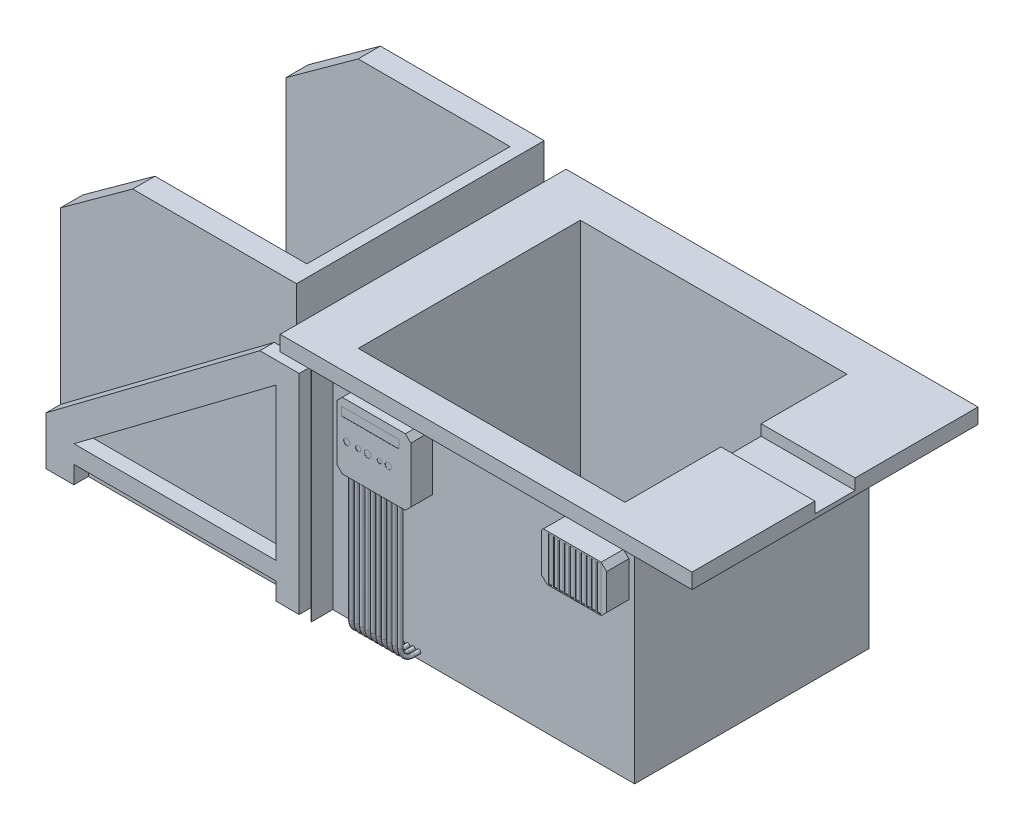
SolidWorks part; units mm, degrees
ref_plane "Alzado" through (0, 0, 0) normal (0, 0, 1) x (1, 0, 0)
ref_plane "Planta" through (0, 0, 0) normal (0, 1, 0) x (1, 0, 0)
ref_plane "Vista lateral" through (0, 0, 0) normal (1, 0, 0) x (0, 0, -1)
sketch "Croquis1" plane through (0, 0, 0) normal (0, 0, 1) x (1, 0, 0)
  line L0 (-486.3336, -748) -> (-486.3336, 440.4157)
  line L1 (-486.3336, 440.4157) -> (-581.0592, 440.4157)
  line L2 (-581.0592, 440.4157) -> (-581.0592, 750)
  line L3 (-581.0592, 750) -> (-1487.3699, 750)
  line L4 (-1487.3699, 750) -> (-1887.0592, 460.4271)
  line L5 (-1887.0592, 460.4271) -> (-1887.0592, -750)
  line L6 (-1887.0592, -750) -> (-486.3336, -748)
  line L7 (-420.4739, -748) -> (1252.9994, -748)
  line L8 (1252.9994, -748) -> (1252.9994, 484)
  line L9 (1252.9994, 484) -> (1887.0592, 484)
  line L10 (1887.0592, 484) -> (1887.0592, 568.1361)
  line L11 (1887.0592, 568.1361) -> (-565.7037, 568.1361)
  line L12 (-565.7037, 568.1361) -> (-565.7037, 491.7844)
  line L13 (-565.7037, 491.7844) -> (-420.4739, 491.7844)
  line L14 (-420.4739, 491.7844) -> (-420.4739, -748)
extrude "Saliente-Extruir1" add sketch "Croquis1" against normal blind 1530
sketch "Croquis2" plane through (0, 568.1361, 0) normal (0, 1, 0) x (1, 0, 0)
  line L1 (1193.3028, 122.6995) -> (-282.0081, 122.6995)
  line L2 (1193.3028, 122.6995) -> (1193.3028, 1350.7139)
  line L3 (1193.3028, 1350.7139) -> (-282.0081, 1350.7139)
  line L4 (-282.0081, 122.6995) -> (-282.0081, 1350.7139)
  line L5 (1193.3028, 122.6995) -> (-282.0081, 1350.7139) construction
  line L6 (1193.3028, 1350.7139) -> (-282.0081, 122.6995) construction
  point P0 (455.6474, 736.7067)
extrude "Cortar-Extruir1" cut sketch "Croquis2" against normal blind 1282
sketch "Croquis3" plane through (1252.9994, 0, 0) normal (1, 0, 0) x (0, 0, -1)
  line L0 (0, 484) -> (116.522, 484)
  line L1 (1530, 484) -> (0, 484) construction
  line L2 (116.522, 484) -> (116.522, -748)
  line L3 (1530, -748) -> (0, -748) construction
  line L4 (116.522, -748) -> (0, -748)
  line L5 (0, -748) -> (0, 484)
  line L6 (765, -748) -> (765, -543.7239) construction
  line L7 (1530, -748) -> (1530, 484)
  line L8 (1413.478, -748) -> (1530, -748)
  line L9 (1413.478, 484) -> (1413.478, -748)
  line L10 (1530, 484) -> (1413.478, 484)
extrude "Cortar-Extruir2" cut sketch "Croquis3" against normal blind 1670
sketch "Croquis4" plane through (0, 0, -116.522) normal (0, 0, 1) x (1, 0, 0)
  line L0 (861.0769, 334.6858) -> (871.0769, 344.6858)
  line L1 (871.0769, 344.6858) -> (1190.8575, 344.6858)
  line L2 (861.0769, 334.6858) -> (861.0769, 118.5117)
  line L3 (891.0769, 88.5117) -> (1190.8575, 88.5117)
  line L4 (1220.8575, 314.6858) -> (1220.8575, 118.5117)
  line L5 (861.0769, 344.6858) -> (1220.8575, 88.5117) construction
  line L6 (861.0769, 88.5117) -> (1220.8575, 344.6858) construction
  line L7 (861.0769, 118.5117) -> (891.0769, 88.5117)
  line L8 (1190.8575, 88.5117) -> (1220.8575, 118.5117)
  line L9 (1190.8575, 344.6858) -> (1220.8575, 314.6858)
  point P0 (1040.9672, 216.5988)
extrude "Saliente-Extruir2" add sketch "Croquis4" along normal blind 123
sketch "Croquis5" plane through (0, 0, 6.478) normal (0, 0, 1) x (1, 0, 0)
  line L1 (898.2664, 335.975) -> (920.0227, 335.975)
  line L2 (898.2664, 335.975) -> (898.2664, 94.2375)
  line L3 (898.2664, 94.2375) -> (920.0227, 94.2375)
  line L4 (920.0227, 335.975) -> (920.0227, 94.2375)
  line L5 (898.2664, 335.975) -> (920.0227, 94.2375) construction
  line L6 (898.2664, 94.2375) -> (920.0227, 335.975) construction
  point P0 (909.1446, 215.1062)
extrude "Cortar-Extruir3" cut sketch "Croquis5" against normal blind 3
pattern_linear "MatrizL1" count 10 spacing 30 along (1, 0, 0) of "Cortar-Extruir3"
sketch "Croquis6" plane through (0, 0, -116.522) normal (0, 0, 1) x (1, 0, 0)
  line L0 (-275.5084, 384.3804) -> (-245.5084, 414.3804)
  line L1 (-245.5084, 414.3804) -> (103.6499, 414.3804)
  line L2 (-275.5084, 384.3804) -> (-275.5084, 77.8428)
  line L3 (-245.5084, 47.8428) -> (103.6499, 47.8428)
  line L4 (133.6499, 384.3804) -> (133.6499, 77.8428)
  line L5 (-275.5084, 414.3804) -> (133.6499, 47.8428) construction
  line L6 (-275.5084, 47.8428) -> (133.6499, 414.3804) construction
  line L7 (-275.5084, 77.8428) -> (-245.5084, 47.8428)
  line L8 (103.6499, 47.8428) -> (133.6499, 77.8428)
  line L9 (103.6499, 414.3804) -> (133.6499, 384.3804)
  point P0 (-70.9292, 231.1116)
extrude "Saliente-Extruir3" add sketch "Croquis6" along normal blind 119
sketch "Croquis7" plane through (0, 0, 2.478) normal (0, 0, 1) x (1, 0, 0)
  line L1 (-250.1754, 369.377) -> (66.9061, 369.377)
  line L2 (-250.1754, 369.377) -> (-250.1754, 322.8717)
  line L3 (-250.1754, 322.8717) -> (66.9061, 322.8717)
  line L4 (66.9061, 369.377) -> (66.9061, 322.8717)
  line L5 (-250.1754, 369.377) -> (66.9061, 322.8717) construction
  line L6 (-250.1754, 322.8717) -> (66.9061, 369.377) construction
  circle A0 centre (-220.5812, 212.9501) radius 17.4315
  circle A1 centre (-157.1648, 212.9501) radius 14.9474
  circle A2 centre (-104.3179, 212.9501) radius 19.0249
  circle A3 centre (-39.4454, 212.9501) radius 12.7548
  circle A4 centre (8.7088, 212.9501) radius 17.2644
  point P0 (-91.6347, 346.1243)
extrude "Cortar-Extruir4" cut sketch "Croquis7" against normal blind 1
sketch "Croquis8" plane through (0, 47.8428, 0) normal (0, -1, 0) x (1, 0, 0)
  circle A0 centre (-211.2082, -14.1362) radius 11.1714
sketch3d "Croquis3D1"
  line L0 (-211.2082, 47.8428, -14.1362) -> (-211.2082, -640.3653, -14.1362)
  line L1 (-211.2082, -710.3653, -84.1362) -> (-211.2082, -710.3653, -131.3291)
  arc A0 (-211.2082, -640.3653, -14.1362) -> (-211.2082, -710.3653, -84.1362) centre (-211.2082, -640.3653, -84.1362) ccw
  point P6 (-211.2082, -710.3653, -14.1362)
  point P7 (-141.2082, -640.3653, -84.1362)
  dimension "D1" = 70
sweep "Barrer1" add profiles "Croquis8" path "Croquis3D1"
pattern_linear "MatrizL2" count 10 spacing 30 along (1, 0, 0) of "Barrer1"
sketch "Croquis9" plane through (0, 0, 0) normal (0, 0, 1) x (1, 0, 0)
  line L0 (-614.2148, -748.1826) -> (-614.2148, 287.7207)
  line L1 (-1887.0592, -750) -> (-486.3336, -748) construction
  line L2 (-614.2148, 287.7207) -> (-1732.7901, -552.8118)
  line L3 (-1732.7901, -552.8118) -> (-1732.7901, -749.7797)
  line L4 (-1732.7901, -749.7797) -> (-1887.0592, -750)
  line L5 (-1887.0592, -750) -> (-1887.0592, -481.6898)
  line L6 (-1887.0592, 460.4271) -> (-1887.0592, -750) construction
  line L7 (-1887.0592, -481.6898) -> (-704.044, 407.2649)
  line L8 (-704.044, 407.2649) -> (-486.3336, 407.2649)
  line L9 (-486.3336, -748) -> (-486.3336, 440.4157) construction
  line L10 (-1732.7901, -552.8118) -> (-614.2148, -552.8118)
  line L11 (-1732.7901, -651.2957) -> (-614.2148, -651.2957)
  line L12 (-1887.0592, -481.6898) -> (-1887.0592, 460.4271)
  line L13 (-1887.0592, 460.4271) -> (-1487.3699, 750)
  line L14 (-1487.3699, 750) -> (-581.0592, 750)
  line L15 (-581.0592, 750) -> (-581.0592, 440.4157)
  line L16 (-581.0592, 440.4157) -> (-486.3336, 440.4157)
  line L17 (-486.3336, 440.4157) -> (-486.3336, 407.2649)
  line M1 (-1887.0592, -750) -> (-486.3336, -748)
  line M2 (-486.3336, -748) -> (-486.3336, 440.4157)
  line M3 (-486.3336, 440.4157) -> (-581.0592, 440.4157)
  line M4 (-581.0592, 440.4157) -> (-581.0592, 750)
  line M5 (-581.0592, 750) -> (-1487.3699, 750)
  line M6 (-1487.3699, 750) -> (-1887.0592, 460.4271)
  line M7 (-1887.0592, 460.4271) -> (-1887.0592, -750)
extrude "Cortar-Extruir5" cut sketch "Croquis9" against normal blind 80 contours L2 L10 L0 | L7 L8 M2 M3 M4 M5 M6 M7 | L11 L3 L0 M1
sketch "Croquis10" plane through (0, 0, -1530) normal (0, 0, -1) x (-1, 0, 0)
  line L0 (614.2148, -552.8118) -> (614.2148, 287.7207)
  line L1 (614.2148, 287.7207) -> (1732.7901, -552.8118)
  line L2 (1732.7901, -552.8118) -> (614.2148, -552.8118)
  line L3 (614.2148, -651.2957) -> (614.2148, -748.1826)
  line L4 (1732.7901, -651.2957) -> (614.2148, -651.2957) construction
  line L5 (614.2148, -748.1826) -> (614.2148, -651.2957) construction
  line L6 (614.2148, -748.1826) -> (1732.7901, -749.7797)
  line L7 (1732.7901, -749.7797) -> (1732.7901, -651.2957)
  line L8 (1732.7901, -651.2957) -> (1732.7901, -749.7797) construction
  line L9 (1732.7901, -651.2957) -> (614.2148, -651.2957)
  line L10 (486.3336, 407.2649) -> (486.3336, 440.4157)
  line L11 (486.3336, 440.4157) -> (581.0592, 440.4157)
  line L12 (581.0592, 440.4157) -> (581.0592, 750)
  line L13 (581.0592, 750) -> (1487.3699, 750)
  line L14 (1487.3699, 750) -> (1887.0592, 460.4271)
  line L15 (1887.0592, 460.4271) -> (1887.0592, -481.6898)
  line L16 (1887.0592, -481.6898) -> (704.044, 407.2649)
  line L17 (704.044, 407.2649) -> (486.3336, 407.2649)
extrude "Cortar-Extruir6" cut sketch "Croquis10" against normal blind 80
sketch "Croquis11" plane through (-1887.0592, 0, 0) normal (-1, 0, 0) x (0, 0, 1)
  line L1 (-1327.2179, 858.529) -> (-203.1999, 858.529)
  line L2 (-1327.2179, 858.529) -> (-1327.2179, -444.7801)
  line L3 (-1327.2179, -444.7801) -> (-203.1999, -444.7801)
  line L4 (-203.1999, 858.529) -> (-203.1999, -444.7801)
  line L5 (-1327.2179, 858.529) -> (-203.1999, -444.7801) construction
  line L6 (-1327.2179, -444.7801) -> (-203.1999, 858.529) construction
  point P0 (-765.2089, 206.8745)
extrude "Cortar-Extruir7" cut sketch "Croquis11" against normal blind 1240
sketch "Croquis12" plane through (-1887.0592, 0, 0) normal (-1, 0, 0) x (0, 0, 1)
  line L1 (-1456.6234, -513.7941) -> (-73.3766, -513.7941)
  line L2 (-1456.6234, -513.7941) -> (-1456.6234, -547.0494)
  line L3 (-1456.6234, -547.0494) -> (-73.3766, -547.0494)
  line L4 (-73.3766, -513.7941) -> (-73.3766, -547.0494)
  line L5 (-1456.6234, -513.7941) -> (-73.3766, -547.0494) construction
  line L6 (-1456.6234, -547.0494) -> (-73.3766, -513.7941) construction
  point P0 (-765, -530.4218)
extrude "Cortar-Extruir8" cut sketch "Croquis12" against normal blind 5
sketch "Croquis13" plane through (1887.0592, 0, 0) normal (1, 0, 0) x (0, 0, -1)
  line L0 (0, 484) -> (1530, 484)
  line L1 (1530, 484) -> (1413.478, 484) construction
  line L2 (1530, 484) -> (0, 484) construction
  line L3 (1530, 484) -> (1530, 568.1361)
  line L4 (1530, 568.1361) -> (0, 568.1361)
  line L5 (0, 568.1361) -> (0, 484)
extrude "Cortar-Extruir9" cut sketch "Croquis13" against normal blind 174.12
sketch "Croquis14" plane through (0, 568.1361, 0) normal (0, 1, 0) x (1, 0, 0)
  line L0 (1193.3028, 122.6995) -> (1193.3028, 1350.7139) construction
  line L1 (1712.9392, 653.9599) -> (1193.3028, 653.9599)
  line L2 (1712.9392, 653.9599) -> (1712.9392, 876.0401)
  line L3 (1712.9392, 876.0401) -> (1193.3028, 876.0401)
  line L4 (1193.3028, 653.9599) -> (1193.3028, 876.0401)
  line L5 (1712.9392, 653.9599) -> (1193.3028, 876.0401) construction
  line L6 (1712.9392, 876.0401) -> (1193.3028, 653.9599) construction
  line L7 (1712.9392, 1530) -> (1712.9392, 0) construction
  point P0 (1453.121, 765)
  point P7 (1712.9392, 876.0401)
extrude "Cortar-Extruir10" cut sketch "Croquis14" against normal blind 60.12
sketch "Croquis15" plane through (0, 568.1361, 0) normal (0, 1, 0) x (1, 0, 0)
  line L0 (1712.9392, 765) -> (-565.7037, 765) construction
  line L1 (1712.9392, 653.9599) -> (1712.9392, 876.0401) construction
  line L2 (-565.7037, 1530) -> (-565.7037, 0) construction
  line L3 (-565.7037, 0) -> (-565.7037, -26)
  line L4 (-565.7037, -26) -> (1712.9392, -26)
  line L5 (1712.9392, -26) -> (1712.9392, 0)
  line L6 (1712.9392, 0) -> (-565.7037, 0)
  line L7 (1712.9392, 1530) -> (-565.7037, 1530)
  line L8 (1712.9392, 1556) -> (1712.9392, 1530)
  line L9 (-565.7037, 1556) -> (1712.9392, 1556)
  line L10 (-565.7037, 1530) -> (-565.7037, 1556)
  dimension "D1" = 26
extrude "Saliente-Extruir4" add sketch "Croquis15" against normal blind 84.12
